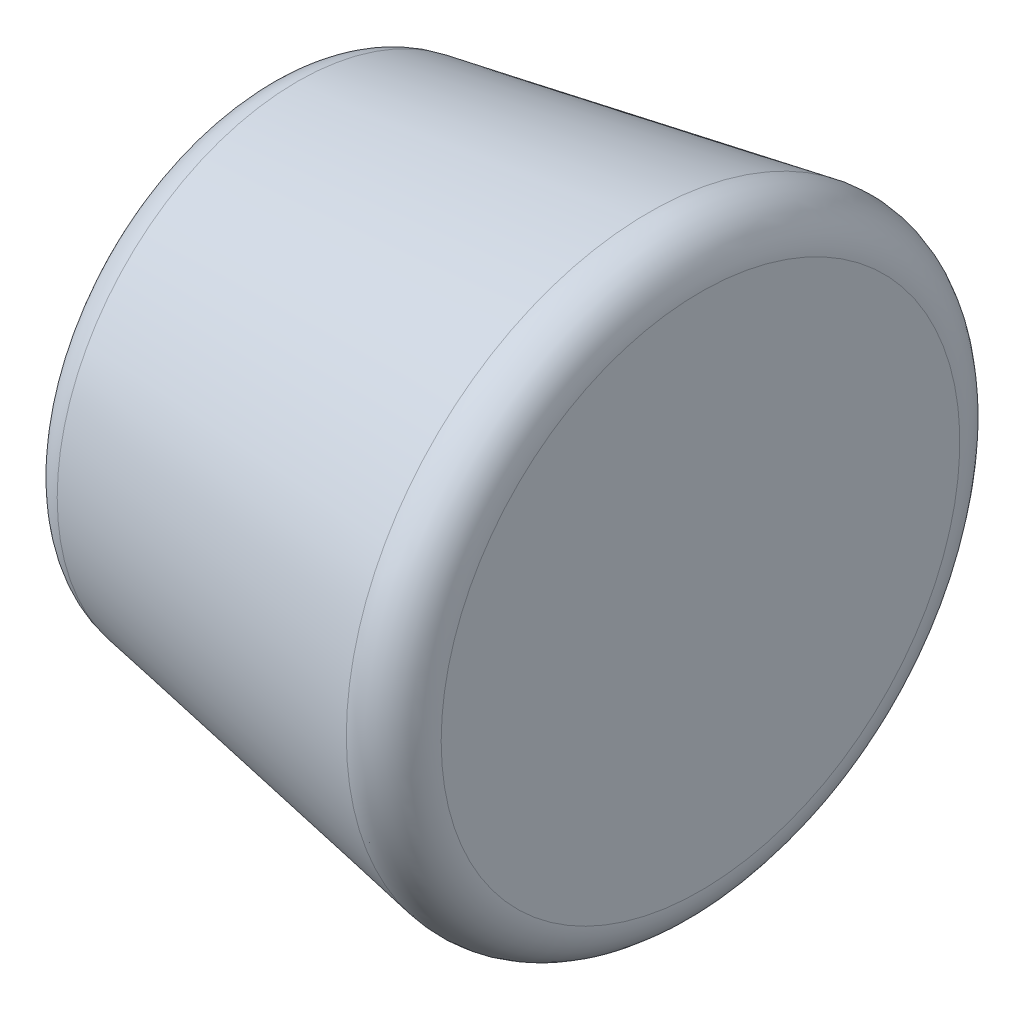
SolidWorks part; units mm, degrees
ref_plane "Front Plane" through (0, 0, 0) normal (0, 0, 1) x (1, 0, 0)
ref_plane "Top Plane" through (0, 0, 0) normal (0, 1, 0) x (1, 0, 0)
ref_plane "Right Plane" through (0, 0, 0) normal (1, 0, 0) x (0, 0, -1)
sketch "Sketch1" plane through (0, 0, 0) normal (0, 0, 1) x (1, 0, 0)
  line L0 (0, 0) -> (0, 5.323)
  line L1 (55, 0) -> (-55, 0) construction
  line L2 (0, 5.323) -> (10, 7.096)
  line L3 (10, 7.096) -> (10, 0)
  line L4 (10, 0) -> (0, 0)
  line L5 (0, 5.323) -> (10, 5.323)
  line L6 (0, -55) -> (0, 55) construction
  point P7 (7.913, 5.323)
  dimension "D1" = 5.323
  dimension "D2" = 7.096
  dimension "D3" = 10
revolve "Revolve1" add sketch "Sketch1" angle 360 about L4
fillet "Fillet1" radius 1 2 edges at (0, 0, -5.323) (10, 0, -7.096)
